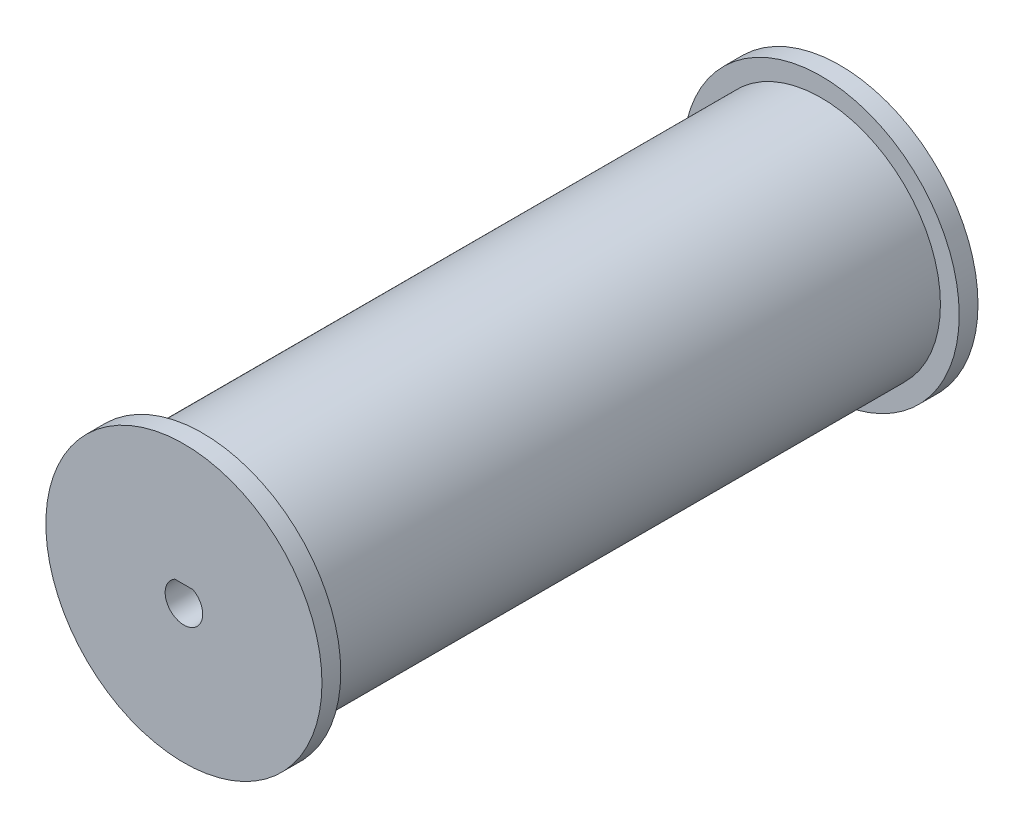
SolidWorks part; units mm, degrees
ref_plane "Front Plane" through (0, 0, 0) normal (0, 0, 1) x (1, 0, 0)
ref_plane "Top Plane" through (0, 0, 0) normal (0, 1, 0) x (1, 0, 0)
ref_plane "Right Plane" through (0, 0, 0) normal (1, 0, 0) x (0, 0, -1)
sketch "Sketch1" plane through (0, 0, 0) normal (0, 0, 1) x (1, 0, 0)
  circle A0 centre (0, 0) radius 12.7
  dimension "D1" = 25.4
extrude "Boss-Extrude1" add sketch "Sketch1" along normal blind 69.85 contours A0
sketch "Sketch2" plane through (0, 0, 69.85) normal (0, 0, 1) x (1, 0, 0)
  line L0 (0, 12.7) -> (0, -12.7) construction
  line L1 (-0.9682, 1.75) -> (0.9682, 1.75)
  circle A0 centre (0, 0) radius 12.7 construction
  arc A1 (-0.9682, 1.75) -> (0.9682, 1.75) centre (0, 0) ccw
  point P8 (0, 1.75)
  dimension "D1" = 2
  dimension "D2" = 1.75
extrude "Cut-Extrude1" cut sketch "Sketch2" against normal blind 10
sketch "Sketch3" plane through (0, 0, 0) normal (0, 0, -1) x (-1, 0, 0)
  circle A0 centre (0, 0) radius 3
  dimension "D1" = 6
extrude "Cut-Extrude2" cut sketch "Sketch3" against normal blind 34.925
sketch "Sketch5" plane through (0, 0, 0) normal (0, 0, 1) x (1, 0, 0)
  circle A0 centre (0, 0) radius 14.7
  circle A2 centre (0, 0) radius 3
extrude "Boss-Extrude2" add sketch "Sketch5" along normal blind 2 contours A2 | A0
sketch "Sketch8" plane through (0, 0, 0) normal (0, 0, 1) x (1, 0, 0)
  line L0 (-0.9682, 1.75) -> (0.9682, 1.75)
  circle A0 centre (0, 0) radius 14.7
  arc A1 (-0.9682, 1.75) -> (0.9682, 1.75) centre (0, 0) ccw
extrude "Boss-Extrude5" add sketch "Sketch8" against normal blind 2 from surface at 69.85 starting at face at (0, -0.125, 69.85)
